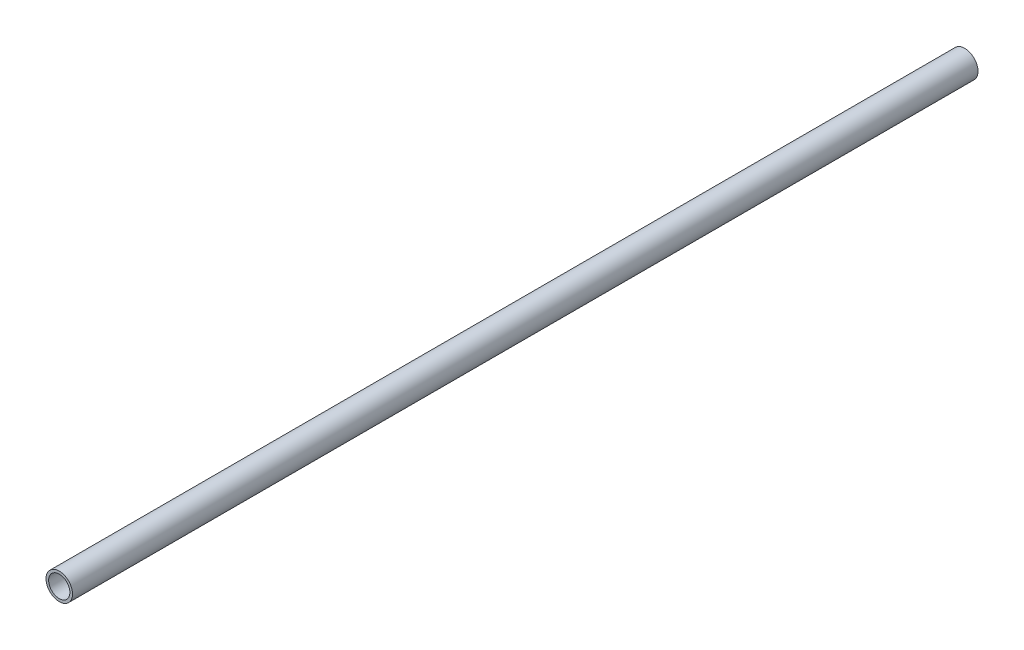
SolidWorks part; units mm, degrees
ref_plane "Front Plane" through (0, 0, 0) normal (0, 0, 1) x (1, 0, 0)
ref_plane "Top Plane" through (0, 0, 0) normal (0, 1, 0) x (1, 0, 0)
ref_plane "Right Plane" through (0, 0, 0) normal (1, 0, 0) x (0, 0, -1)
sketch "Sketch3" plane through (0, 0, 40.7745) normal (0, 0, -1) x (-1, 0, 0)
  circle A0 centre (0, 0) radius 7.9375
  circle A1 centre (0, 0) radius 6.35
  arc A2 (-2.3597, -7.5786) -> (2.3597, 7.5786) centre (0, 0) ccw construction
  arc A3 (-1.8877, -6.0629) -> (1.8877, 6.0629) centre (0, 0) ccw construction
extrude "Boss-Extrude2" add sketch "Sketch3" along normal up to surface (542.0274 mm away)
